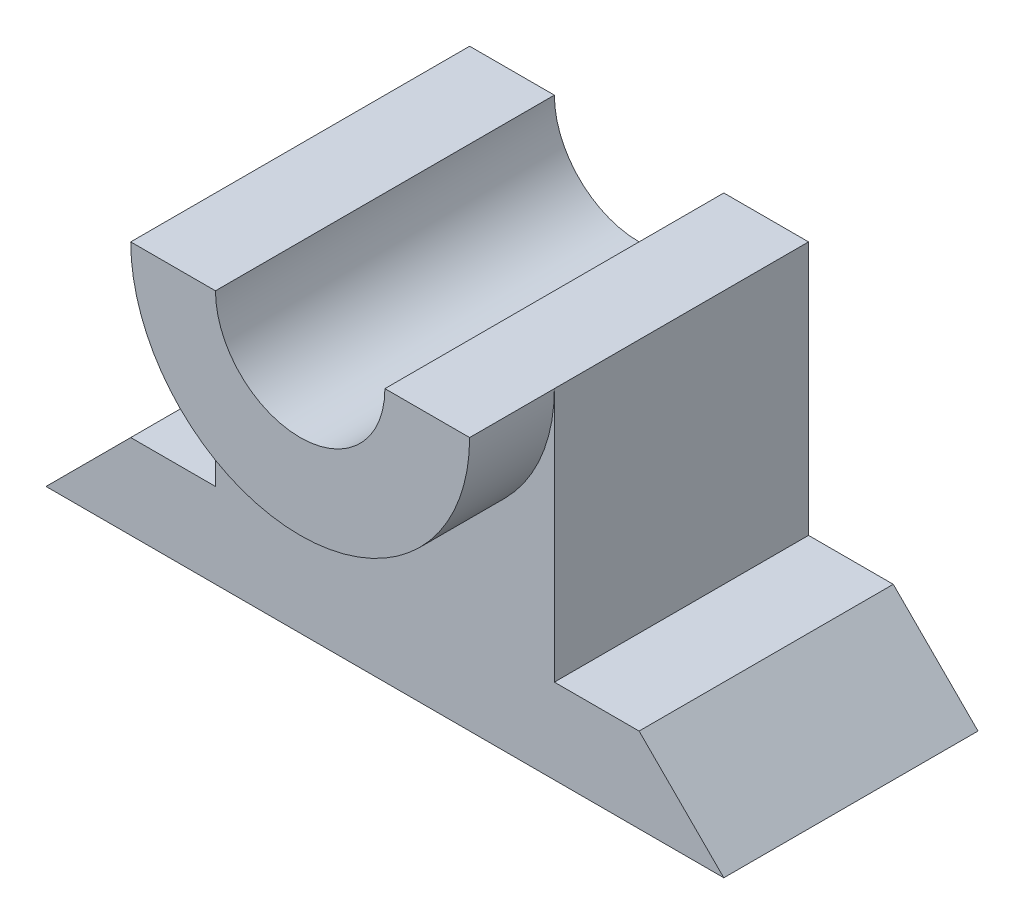
SolidWorks part; units mm, degrees
ref_plane "前基準面" through (0, 0, 0) normal (0, 0, 1) x (1, 0, 0)
ref_plane "上基準面" through (0, 0, 0) normal (0, 1, 0) x (1, 0, 0)
ref_plane "右基準面" through (0, 0, 0) normal (1, 0, 0) x (0, 0, -1)
sketch "草圖1" plane through (0, 0, 0) normal (0, 0, 1) x (1, 0, 0)
  line L0 (-10, 0) -> (-5, 0)
  line L1 (10, 0) -> (10, -15)
  line L2 (10, -15) -> (15, -15)
  line L3 (15, -15) -> (20, -20)
  line L4 (20, -20) -> (-20, -20)
  line L5 (0, -20) -> (0, 0) construction
  line L6 (-15, -15) -> (-20, -20)
  line L7 (-10, -15) -> (-15, -15)
  line L8 (-10, 0) -> (-10, -15)
  line L9 (5, 0) -> (10, 0)
  arc A0 (-5, 0) -> (5, 0) centre (0, 0) ccw
  point P11 (0, 0)
  dimension "D6" = 10
  dimension "D1" = 10
  dimension "D2" = 20
  dimension "D3" = 15
  dimension "D4" = 5
  dimension "D5" = 20
extrude "填料-伸長1" add sketch "草圖1" along normal mid plane 15
sketch "草圖3" plane through (0, 0, 7.5) normal (0, 0, 1) x (1, 0, 0)
  line L0 (-10, 0) -> (-5, 0)
  line L1 (5, 0) -> (10, 0)
  arc A0 (-10, 0) -> (10, 0) centre (0, 0) ccw
  arc A1 (-5, 0) -> (5, 0) centre (0, 0) ccw construction
  arc A2 (-5, 0) -> (5, 0) centre (0, 0) ccw
extrude "填料-伸長2" add sketch "草圖3" along normal blind 5
